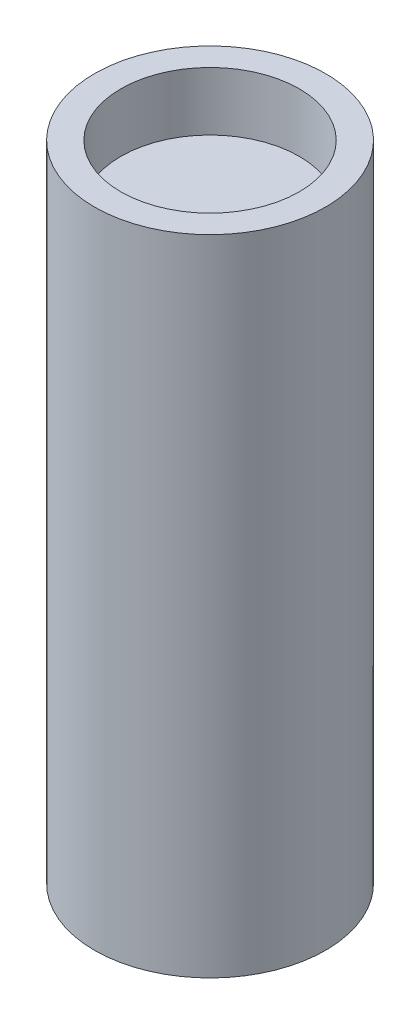
SolidWorks part; units mm, degrees
ref_plane "前视基准面" through (0, 0, 0) normal (0, 0, 1) x (1, 0, 0)
ref_plane "上视基准面" through (0, 0, 0) normal (0, 1, 0) x (1, 0, 0)
ref_plane "右视基准面" through (0, 0, 0) normal (1, 0, 0) x (0, 0, -1)
other "Configuration Table"
sketch "草图2" plane through (0, 0, 0) normal (0, 1, 0) x (1, 0, 0)
  circle A0 centre (0, 0) radius 3.95
  dimension "D1" = 7.9
extrude "凸台-拉伸1" add sketch "草图2" along normal blind 20
sketch "草图8" plane through (0, 20, 0) normal (0, 1, 0) x (1, 0, 0)
  circle A0 centre (0, 0) radius 3.05
  circle A1 centre (0, 0) radius 3.95
  circle A2 centre (0, 0) radius 3.95 construction
  dimension "D1" = 6.1
extrude "凸台-拉伸3" add sketch "草图8" along normal blind 2
